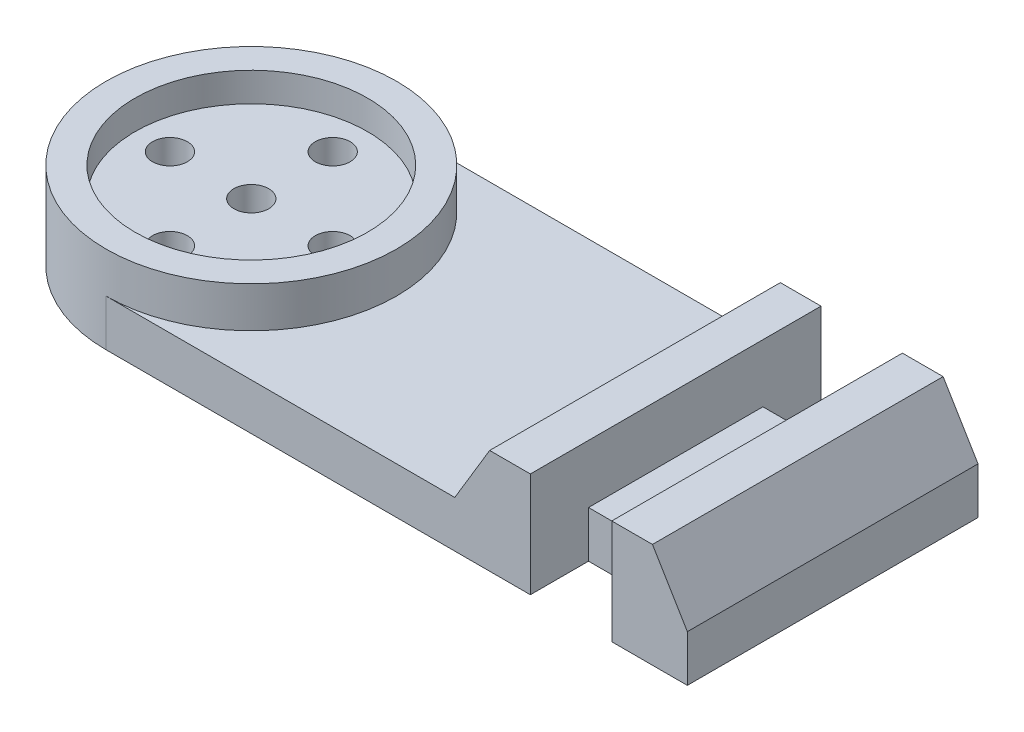
SolidWorks part; units mm, degrees
material "ABS"
ref_plane "前视基准面" through (0, 0, 0) normal (0, 0, 1) x (1, 0, 0)
ref_plane "上视基准面" through (0, 0, 0) normal (0, 1, 0) x (1, 0, 0)
ref_plane "右视基准面" through (0, 0, 0) normal (1, 0, 0) x (0, 0, -1)
sketch "草图1" plane through (0, 0, 0) normal (0, 1, 0) x (1, 0, 0)
  line L0 (0, 12.5) -> (50, 12.5)
  line L1 (0, -12.5) -> (50, -12.5)
  line L2 (50, 12.5) -> (50, -12.5)
  circle A0 centre (0, 0) radius 12.5
  dimension "D1" = 25
  dimension "D2" = 50
extrude "凸台-拉伸1" add sketch "草图1" along normal blind 4 contours A0 | A0 L1 L2 L0
sketch "草图2" plane through (0, 4, 0) normal (0, 1, 0) x (1, 0, 0)
  circle A0 centre (0, 0) radius 12.5
  circle A1 centre (0, 0) radius 10
  dimension "D1" = 25
  dimension "D2" = 20
extrude "凸台-拉伸2" add sketch "草图2" along normal blind 3.5
sketch "草图3" plane through (0, 0, 0) normal (0, -1, 0) x (1, 0, 0)
  line L0 (0, 16.9978) -> (0, -21.3221) construction
  line L1 (-30.6103, 0) -> (69.188, 0) construction
  circle A0 centre (0, 0) radius 1.5
  circle A1 centre (0, 7) radius 1.5
  circle A2 centre (7, 0) radius 1.5
  circle A3 centre (0, -7) radius 1.5
  circle A4 centre (-7, 0) radius 1.5
  circle A5 centre (40, 0) radius 1.5
  dimension "D1" = 3
  dimension "D2" = 3
  dimension "D5" = 3
  dimension "D3" = 7
  dimension "D6" = 40
  dimension "D4" = 4
extrude "切除-拉伸1" cut sketch "草图3" against normal through all
sketch "草图4" plane through (0, 0, 12.5) normal (0, 0, 1) x (1, 0, 0)
  line L0 (40, 14.1176) -> (40, -14.2645) construction
  line L2 (50, 4) -> (47, 9)
  line L3 (47, 9) -> (33, 9)
  line L4 (0, 4) -> (50, 4) construction
  line L5 (30, 4) -> (33, 9)
  line L6 (30, 4) -> (50, 4)
  point P11 (40, 9)
  dimension "D1" = 40
  dimension "D2" = 7
  dimension "D3" = 5
extrude "凸台-拉伸3" add sketch "草图4" against normal up to surface (25 mm away) up to face at (25, 2, -12.5)
sketch "草图5" plane through (0, 0, 12.5) normal (0, 0, 1) x (1, 0, 0)
  line L0 (40, 19.3346) -> (40, -11.3346) construction
  line L1 (36.5, 9) -> (43.5, 9)
  line L2 (47, 9) -> (33, 9) construction
  line L3 (43.5, 9) -> (43.5, 4)
  line L4 (43.5, 4) -> (36.5, 4)
  line L5 (36.5, 9) -> (36.5, 4)
  point P10 (40, 4)
  point P11 (40, 9)
  dimension "D1" = 40
  dimension "D2" = 3.5
  dimension "D3" = 5
extrude "切除-拉伸2" cut sketch "草图5" against normal through all
sketch "草图6" plane through (0, 4, 0) normal (0, 1, 0) x (1, 0, 0)
  line L0 (36.5, -12.5) -> (43.5, -12.5)
  line L1 (43.5, -12.5) -> (43.5, -7.5)
  line L2 (43.5, -7.5) -> (36.5, -7.5)
  line L3 (36.5, 12.5) -> (36.5, -12.5) construction
  line L4 (36.5, -7.5) -> (36.5, -12.5)
  line L5 (-16.7425, 0) -> (62.5585, 0) construction
  line L6 (36.5, 12.5) -> (43.5, 12.5)
  line L7 (36.5, 7.5) -> (36.5, 12.5)
  line L8 (43.5, 12.5) -> (43.5, 7.5)
  line L9 (43.5, 7.5) -> (36.5, 7.5)
  dimension "D1" = 5
extrude "切除-拉伸3" cut sketch "草图6" against normal through all
sketch "草图7" plane through (0, 4, 0) normal (0, 1, 0) x (1, 0, 0)
  circle A0 centre (0, 0) radius 10
  circle A1 centre (0, 0) radius 1.5
  circle A2 centre (0, 7) radius 1.5
  circle A3 centre (7, 0) radius 1.5
  circle A4 centre (0, -7) radius 1.5
  circle A6 centre (-7, 0) radius 1.5
extrude "凸台-拉伸4" add sketch "草图7" along normal blind 1
